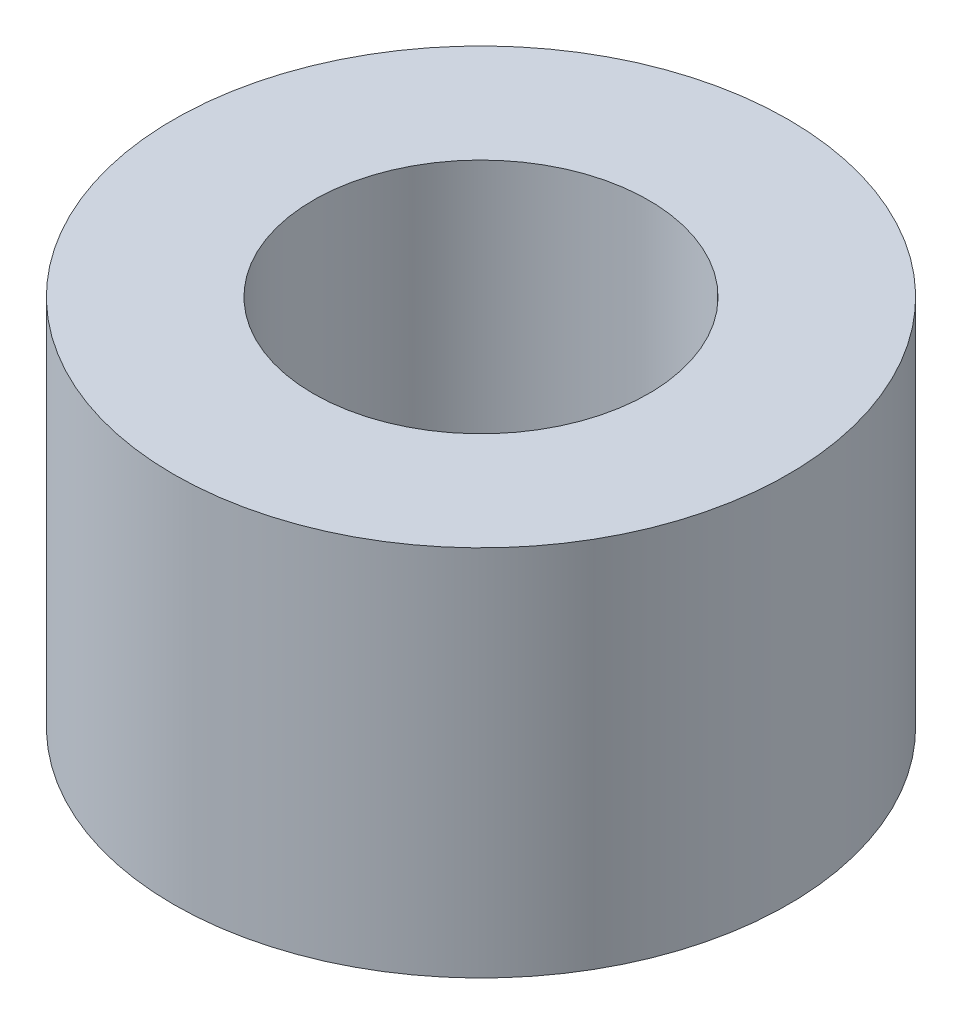
SolidWorks part; units mm, degrees
ref_plane "Front Plane" through (0, 0, 0) normal (0, 0, 1) x (1, 0, 0)
ref_plane "Top Plane" through (0, 0, 0) normal (0, 1, 0) x (1, 0, 0)
ref_plane "Right Plane" through (0, 0, 0) normal (1, 0, 0) x (0, 0, -1)
sketch "Sketch1" plane through (0, 0, 0) normal (0, 1, 0) x (1, 0, 0)
  circle A0 centre (0, 0) radius 1.8
  circle A1 centre (0, 0) radius 3.3
  dimension "D1" = 3.6
  dimension "D2" = 6.6
extrude "Boss-Extrude1" add sketch "Sketch1" along normal blind 4
